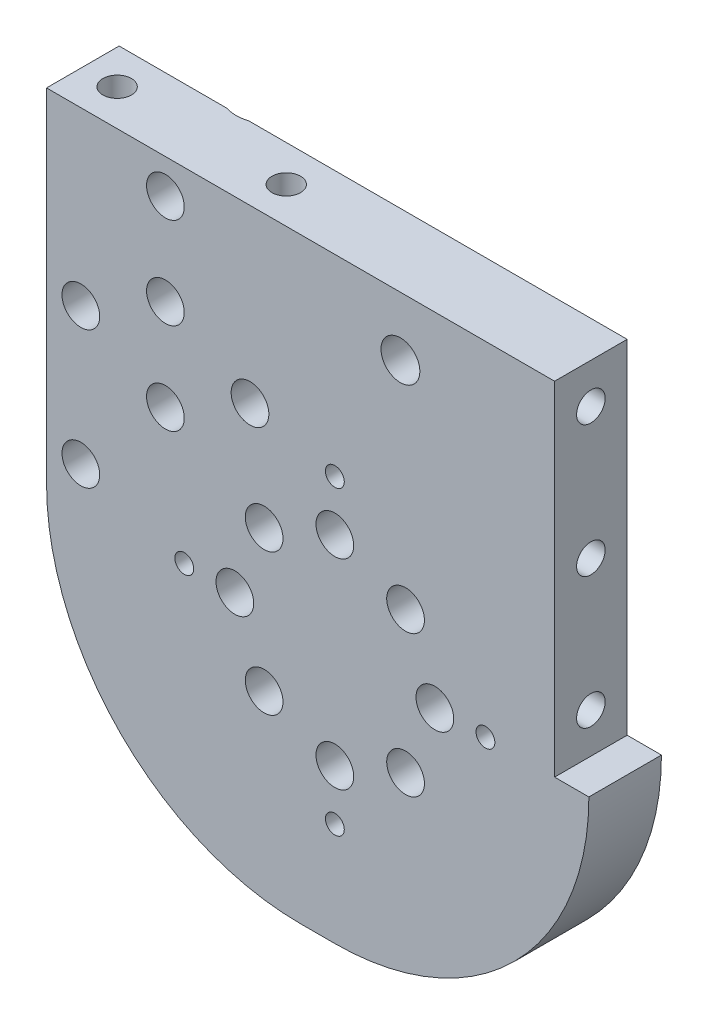
SolidWorks part; units mm, degrees
ref_plane "Front Plane" through (0, 0, 0) normal (0, 0, 1) x (1, 0, 0)
ref_plane "Top Plane" through (0, 0, 0) normal (0, 1, 0) x (1, 0, 0)
ref_plane "Right Plane" through (0, 0, 0) normal (1, 0, 0) x (0, 0, -1)
ref_plane "Plane1" through (0, 0, 0) normal (0, 0, -1) x (-1, 0, 0)
sketch "Sketch1" plane through (0, 0, 0) normal (0, 0, -1) x (-1, 0, 0)
  line L0 (44.45, 0) -> (44.45, 60)
  line L1 (44.45, 60) -> (-44.45, 60)
  line L2 (-44.45, 60) -> (-44.45, 0)
  arc A0 (-44.45, 0) -> (44.45, 0) centre (0, 0) ccw
extrude "Boss-Extrude1" add sketch "Sketch1" against normal blind 12.7
hole_wizard "#4 Clearance Hole1" positions "Sketch3" profile "Sketch2" hole size "#4" standard "ANSI Inch"
sketch "Sketch3" plane through (0, 0, 12.7) normal (0, 0, 1) x (1, 0, 0)
  line L0 (6, 0) -> (6, 26.35) construction
  line L1 (6, 0) -> (32.35, 0) construction
  line L2 (6, 0) -> (6, -26.35) construction
  line L3 (6, 0) -> (-20.35, 0) construction
  circle A0 centre (6, 0) radius 26.35 construction
  point P0 (32.35, 0.009)
  point P1 (6, -26.35)
  point P2 (-20.35, -0.01)
  point P3 (6, 26.35)
  dimension "D1" = 52.7
  dimension "D2" = 6
sketch "Sketch2" plane through (32.35, 0.009, 12.7) normal (1, 0, 0) x (0, -1, 0)
  line L0 (0, 0) -> (0, 12.7)
  line L1 (0, 12.7) -> (1.65, 12.7)
  line L2 (1.65, 12.7) -> (1.65, 0)
  line L5 (1.65, 0) -> (0, 0)
  line L11 (0, -6.35) -> (0, 107.95) construction
  dimension "Thru Hole Dia." = 3.3
  dimension "Thru Hole Depth" = 12.7
hole_wizard "1/4 Clearance Hole1" positions "Sketch5" profile "Sketch4" hole size "1/4" standard "ANSI Inch"
sketch "Sketch5" plane through (0, 0, 0) normal (0, 0, -1) x (-1, 0, 0)
  point P0 (8.85, 30)
  point P1 (23.65, 38)
  point P2 (23.65, 22)
sketch "Sketch4" plane through (-8.85, 30, 0) normal (1, 0, 0) x (0, 1, 0)
  line L0 (0, 0) -> (0, 12.7)
  line L1 (0, 12.7) -> (3.3, 12.7)
  line L2 (3.3, 12.7) -> (3.3, 0)
  line L5 (3.3, 0) -> (0, 0)
  line L11 (0, -6.35) -> (0, 107.95) construction
  dimension "Thru Hole Dia." = 6.6
  dimension "Thru Hole Depth" = 12.7
hole_wizard "1/4 Clearance Hole2" positions "Sketch7" profile "Sketch6" hole size "1/4" standard "ANSI Inch"
sketch "Sketch7" plane through (0, 0, 12.7) normal (0, 0, 1) x (1, 0, 0)
  line L0 (0, 0) -> (0, 60) construction
  line L1 (-44.45, 60) -> (44.45, 60) construction
  point P0 (17.4725, 49.6929)
  dimension "D1" = 17.4725
sketch "Sketch6" plane through (17.4725, 49.6929, 12.7) normal (1, 0, 0) x (0, -1, 0)
  line L0 (0, 0) -> (0, 12.7)
  line L1 (0, 12.7) -> (3.4, 12.7)
  line L2 (3.4, 12.7) -> (3.4, 0)
  line L5 (3.4, 0) -> (0, 0)
  line L11 (0, -6.35) -> (0, 107.95) construction
  dimension "Thru Hole Dia." = 6.8
  dimension "Thru Hole Depth" = 12.7
hole_wizard "CSK for 1/4 Flat Head Machine Screw (100)1" positions "Sketch9" profile "Sketch8" countersink size "1/4" standard "ANSI Inch"
sketch "Sketch9" plane through (0, 0, 0) normal (0, 0, -1) x (-1, 0, 0)
  point P0 (23.65, 54)
  point P1 (38.45, 6)
  point P2 (38.45, 30)
sketch "Sketch8" plane through (-23.65, 54, 0) normal (1, 0, 0) x (0, 1, 0)
  line L0 (0, 0) -> (0, 12.7)
  line L1 (0, 12.7) -> (3.3, 12.7)
  line L2 (3.3, 12.7) -> (3.3, 3)
  line L3 (3.3, 3) -> (6.3, 0)
  line L5 (6.3, 0) -> (0, 0)
  line L6 (-3.3, 3) -> (-6.3, 0) construction
  line L11 (0, -6.35) -> (0, 107.95) construction
  dimension "Thru Hole Dia." = 6.6
  dimension "Thru Hole Depth" = 12.7
  dimension "Near C'Sink Dia." = 12.6
  dimension "Near C'Sink Angle" = 90
hole_wizard "#10 Clearance Hole1" positions "Sketch11" profile "Sketch10" hole size "#10" standard "ANSI Inch"
sketch "Sketch11" plane through (0, 60, 0) normal (0, 1, 0) x (1, 0, 0)
  point P0 (-38.45, -6.35)
  point P1 (-8.85, -6.35)
sketch "Sketch10" plane through (-38.45, 60, 6.35) normal (1, 0, 0) x (0, 0, 1)
  line L0 (0, 0) -> (0, 15)
  line L1 (0, 15) -> (2.5, 15)
  line L2 (2.5, 15) -> (2.5, 0)
  line L5 (2.5, 0) -> (0, 0)
  line L10 (0, 15) -> (-2.5, 15) construction
  line L11 (0, -6.35) -> (0, 107.95) construction
  dimension "Hole Dia." = 5
  dimension "Hole Depth" = 15
  dimension "Drill Angle" = 180
hole_wizard "#10 Clearance Hole2" positions "Sketch13" profile "Sketch12" hole size "#10" standard "ANSI Inch"
sketch "Sketch13" plane through (44.45, 0, 0) normal (1, 0, 0) x (0, 0, -1)
  point P0 (-6.35, 7)
  point P1 (-6.35, 53)
  point P2 (-6.35, 30)
sketch "Sketch12" plane through (44.45, 7, 6.35) normal (0, 1, 0) x (0, 0, -1)
  line L0 (0, 0) -> (0, 10)
  line L1 (0, 10) -> (2.5, 10)
  line L2 (2.5, 10) -> (2.5, 0)
  line L5 (2.5, 0) -> (0, 0)
  line L10 (0, 10) -> (-2.5, 10) construction
  line L11 (0, -6.35) -> (0, 107.95) construction
  dimension "Hole Dia." = 5
  dimension "Hole Depth" = 10
  dimension "Drill Angle" = 180
hole_wizard "1-3/4 Clearance Hole1" positions "Sketch15" profile "Sketch14" hole size "1-3/4" standard "ANSI Inch"
sketch "Sketch15" plane through (0, 0, 0) normal (0, 0, -1) x (-1, 0, 0)
  point P0 (-6, 0)
  dimension "D1" = 6
sketch "Sketch14" plane through (6, 0, 0) normal (1, 0, 0) x (0, 1, 0)
  line L0 (0, 0) -> (0, 5)
  line L1 (0, 5) -> (22.5, 5)
  line L2 (22.5, 5) -> (22.5, 0)
  line L5 (22.5, 0) -> (0, 0)
  line L10 (0, 5) -> (-22.5, 5) construction
  line L11 (0, -6.35) -> (0, 107.95) construction
  dimension "Hole Dia." = 45
  dimension "Hole Depth" = 5
  dimension "Drill Angle" = 180
hole_wizard "1/4 Clearance Hole3" positions "Sketch17" profile "Sketch16" hole size "1/4" standard "ANSI Inch"
sketch "Sketch17" plane through (0, 0, 12.7) normal (0, 0, 1) x (1, 0, 0)
  line L0 (6, 0) -> (6, 17.5) construction
  line L2 (6, 0) -> (-6.3744, 12.3744) construction
  line L4 (6, 0) -> (-11.5, 0) construction
  line L5 (6, 0) -> (-6.3744, -12.3744) construction
  line L6 (6, 0) -> (6, -17.5) construction
  line L7 (6, 0) -> (18.3744, -12.3744) construction
  line L8 (6, 0) -> (23.5, 0) construction
  line L9 (6, 0) -> (18.3744, 12.3744) construction
  circle A0 centre (6, 0) radius 17.5 construction
  point P0 (18.3744, 12.3744)
  point P1 (23.5, -0.0012)
  point P2 (18.3744, -12.3744)
  point P3 (6, -17.5)
  point P4 (-6.3744, -12.3744)
  point P5 (-11.5, 0)
  point P6 (-6.3744, 12.3744)
  point P7 (6, 17.5)
  dimension "D1" = 35
  dimension "D2" = 45
  dimension "D3" = 45
  dimension "D4" = 45
  dimension "D5" = 45
  dimension "D6" = 6
sketch "Sketch16" plane through (18.3744, 12.3744, 12.7) normal (1, 0, 0) x (0, -1, 0)
  line L0 (0, 0) -> (0, 12.7)
  line L1 (0, 12.7) -> (3.3, 12.7)
  line L2 (3.3, 12.7) -> (3.3, 0)
  line L5 (3.3, 0) -> (0, 0)
  line L11 (0, -6.35) -> (0, 107.95) construction
  dimension "Thru Hole Dia." = 6.6
  dimension "Thru Hole Depth" = 12.7
chamfer "Chamfer1" distance 3 angle 45 3 edges at (-26.95, 38, 0) (-12.15, 30, 0) (-26.95, 22, 0)
sketch "Sketch18" plane through (0, 0, 0) normal (0, 0, -1) x (-1, 0, 0)
  line L0 (44.45, 0) -> (-44.45, 0) construction
  line L1 (-44.45, 0) -> (-50.45, 0)
  line L2 (-6, -44.45) -> (0, -44.45)
  arc A0 (-50.45, 0) -> (-6, -44.45) centre (-6, 0) ccw
  arc A1 (-44.45, 0) -> (44.45, 0) centre (0, 0) ccw construction
  arc A2 (-44.45, 0) -> (0, -44.45) centre (0, 0) ccw
  dimension "D1" = 88.9
extrude "Boss-Extrude2" add sketch "Sketch18" against normal up to surface (12.7 mm away) up to face at (21.6744, 12.3744, 12.7)
mirror "镜向1" about plane through (-44.45, 0, 12.7) normal (-1, 0, 0) of bodies 112
sketch "草图1" plane through (0, 0, 0) normal (0, 0, -1) x (-1, 0, 0)
  line L1 (44.45, 70.2036) -> (-82.4243, 70.2036)
  line L2 (44.45, 70.2036) -> (44.45, -60.0997)
  line L3 (44.45, -60.0997) -> (-82.4243, -60.0997)
  line L4 (-82.4243, 70.2036) -> (-82.4243, -60.0997)
extrude "切除-拉伸1" cut sketch "草图1" against normal through all
mirror "镜向3" about plane through (-44.45, 70.2036, 12.7) normal (-1, 0, 0) of bodies 114
sketch "草图4" plane through (0, 0, 12.7) normal (0, 0, 1) x (1, 0, 0)
  line L1 (-44.45, 69.0129) -> (-164.3152, 69.0129)
  line L2 (-44.45, 69.0129) -> (-44.45, -67.0541)
  line L3 (-44.45, -67.0541) -> (-164.3152, -67.0541)
  line L4 (-164.3152, 69.0129) -> (-164.3152, -67.0541)
extrude "切除-拉伸3" cut sketch "草图4" against normal through all
